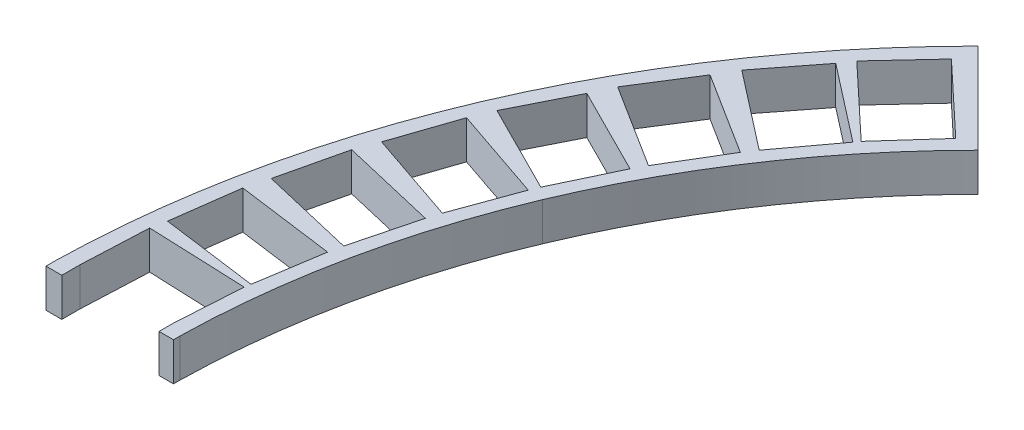
SolidWorks part; units mm, degrees
ref_plane "Front Plane" through (0, 0, 0) normal (0, 0, 1) x (1, 0, 0)
ref_plane "Top Plane" through (0, 0, 0) normal (0, 1, 0) x (1, 0, 0)
ref_plane "Right Plane" through (0, 0, 0) normal (1, 0, 0) x (0, 0, -1)
sketch "Sketch1" plane through (0, 0, 0) normal (0, 1, 0) x (1, 0, 0)
  line L0 (0, -1585.8629) -> (0, 77707.2829) construction
  line L1 (-1585.8629, 0) -> (77707.2829, 0) construction
  line L3 (-208.7307, 208.7307) -> (-180.4465, 180.4465)
  line L38 (0, 0) -> (-235.3327, 98.6832) construction
  line L40 (-289.2273, 29.4116) -> (-290.1702, 8.4325)
  line L41 (-258.3506, 28.1687) -> (-289.2273, 29.4116)
  line L42 (-259.6721, 7.2049) -> (-258.3506, 28.1687)
  line L43 (-288.2865, 34.0691) -> (-258.0332, 30.0089)
  line L44 (-285.4916, 54.8823) -> (-288.2865, 34.0691)
  line L45 (-254.767, 50.7589) -> (-285.4916, 54.8823)
  line L46 (-258.0332, 30.0089) -> (-254.767, 50.7589)
  line L47 (-283.6129, 61.9158) -> (-253.8994, 54.9336)
  line L48 (-278.809, 82.359) -> (-283.6129, 61.9158)
  line L49 (-248.631, 75.2676) -> (-278.809, 82.359)
  line L50 (-253.8994, 54.9336) -> (-248.631, 75.2676)
  line L51 (-276.2559, 89.1768) -> (-247.3613, 79.3409)
  line L52 (-269.4887, 109.0566) -> (-276.2559, 89.1768)
  line L53 (-240.1424, 99.0668) -> (-269.4887, 109.0566)
  line L54 (-247.3613, 79.3409) -> (-240.1424, 99.0668)
  line L57 (-290.1702, 8.4325) -> (-290.1702, 2.7796)
  line L58 (-295.1278, 6.0543) -> (-295.1278, 2.7796)
  line L59 (-259.6721, 7.2049) -> (-259.6721, 2.7796)
  line L60 (-255.1447, 4.794) -> (-255.1447, 2.7796)
  line L62 (-295.1278, 2.7796) -> (-290.1702, 2.7796)
  line L63 (-259.6721, 2.7796) -> (-255.1447, 2.7796)
  line L64 (-259.6721, 2.7796) -> (-255.1447, 2.7796) construction
  line L79 (-229.9678, 120.8198) -> (-238.9775, 101.8448)
  line L80 (-238.9775, 101.8448) -> (-266.6718, 115.7742)
  line L81 (-266.6718, 115.7742) -> (-257.2357, 134.5348)
  line L82 (-257.2357, 134.5348) -> (-229.9678, 120.8198)
  line L83 (-217.1419, 142.5904) -> (-227.9525, 124.5804)
  line L84 (-227.9525, 124.5804) -> (-254.1624, 141.1345)
  line L85 (-254.1624, 141.1345) -> (-242.9484, 158.8896)
  line L86 (-242.9484, 158.8896) -> (-217.1419, 142.5904)
  line L87 (-202.2618, 163.0088) -> (-214.7723, 146.1353)
  line L88 (-214.7723, 146.1353) -> (-239.2485, 165.1595)
  line L89 (-239.2485, 165.1595) -> (-226.3625, 181.7412)
  line L90 (-226.3625, 181.7412) -> (-202.2618, 163.0088)
  line L91 (-187.1454, 180.1612) -> (-201.1717, 164.525)
  line L92 (-201.1717, 164.525) -> (-223.6999, 185.6767)
  line L93 (-223.6999, 185.6767) -> (-209.3974, 201.0536)
  line L94 (-209.3974, 201.0536) -> (-187.1454, 180.1612)
  arc A0 (-259.7741, 0) -> (-259.7272, 4.9386) centre (0, 0) ccw construction
  arc A1 (-295.1278, 6.0543) -> (-208.7307, 208.7307) centre (0, 0) cw
  arc A3 (-259.7741, 0) -> (-259.7272, 4.9386) centre (0, 0) ccw construction
  arc A4 (-259.7741, 0) -> (-259.7272, 4.9386) centre (0, 0) ccw construction
  arc A5 (-259.7741, 0) -> (-259.7272, 4.9386) centre (0, 0) ccw construction
  arc A6 (-259.7741, 0) -> (-259.7272, 4.9386) centre (0, 0) ccw construction
  arc A7 (-259.7741, 0) -> (-259.7272, 4.9386) centre (0, 0) ccw construction
  arc A8 (-259.7741, 0) -> (-259.7272, 4.9386) centre (0, 0) ccw construction
  arc A9 (-259.7741, 0) -> (-259.7272, 4.9386) centre (0, 0) ccw construction
  arc A12 (-259.7741, 0) -> (-259.7272, 4.9386) centre (0, 0) ccw construction
  arc A13 (-259.7741, 0) -> (-259.7272, 4.9386) centre (0, 0) ccw construction
  arc A14 (-259.7741, 0) -> (-259.7272, 4.9386) centre (0, 0) ccw construction
  arc A15 (-259.7741, 0) -> (-259.7272, 4.9386) centre (0, 0) ccw construction
  arc A16 (-259.7741, 0) -> (-259.7272, 4.9386) centre (0, 0) ccw construction
  arc A17 (-259.7741, 0) -> (-259.7272, 4.9386) centre (0, 0) ccw construction
  arc A18 (-259.7741, 0) -> (-259.7272, 4.9386) centre (0, 0) ccw construction
  arc A20 (-235.3327, 98.6832) -> (-180.4465, 180.4465) centre (-0.0002, 0.0123) cw
  arc A21 (-235.3327, 98.6832) -> (-255.1447, 4.794) centre (-0.0089, -0.0085) ccw
  dimension "D3" = 45
  dimension "D22" = 5.9
  dimension "D11" = 8
  dimension "D18" = 8
extrude "Boss-Extrude1" add sketch "Sketch1" along normal blind 12
